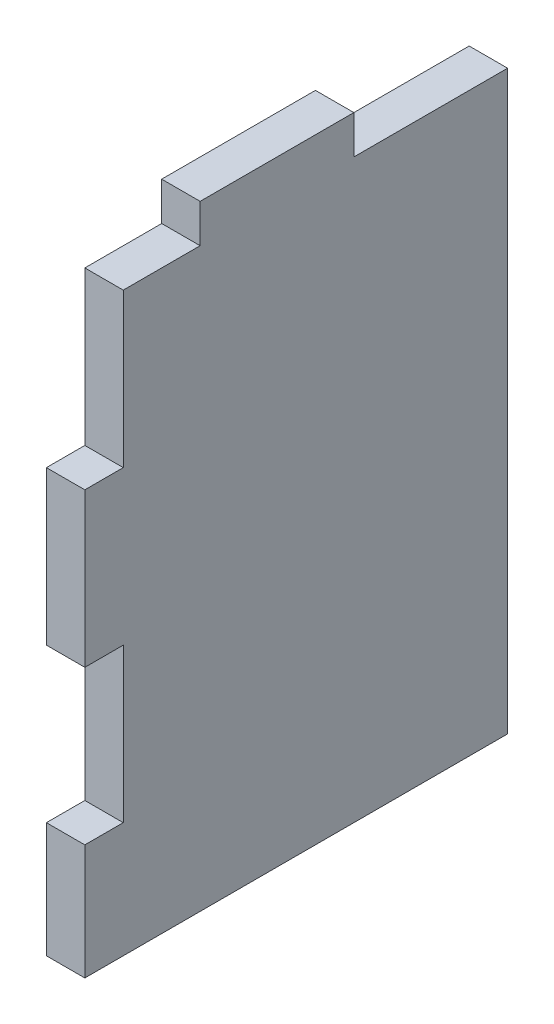
SolidWorks part; units mm, degrees
ref_plane "Front Plane" through (0, 0, 0) normal (0, 0, 1) x (1, 0, 0)
ref_plane "Top Plane" through (0, 0, 0) normal (0, 1, 0) x (1, 0, 0)
ref_plane "Right Plane" through (0, 0, 0) normal (1, 0, 0) x (0, 0, -1)
sketch "Sketch1" plane through (0, 0, 0) normal (1, 0, 0) x (0, 0, -1)
  line L0 (-3.175, 0) -> (0, 0)
  line L1 (0, 0) -> (31.75, 0)
  line L2 (0, 0) -> (0, 47.625)
  line L3 (0, 47.625) -> (31.75, 47.625)
  line L4 (31.75, 0) -> (31.75, 47.625)
  line L5 (6.35, 47.625) -> (19.05, 47.625)
  line L6 (6.35, 47.625) -> (6.35, 50.8)
  line L7 (6.35, 50.8) -> (19.05, 50.8)
  line L8 (19.05, 47.625) -> (19.05, 50.8)
  line L9 (0, 34.925) -> (-3.175, 34.925)
  line L10 (0, 34.925) -> (0, 22.225)
  line L11 (0, 22.225) -> (-3.175, 22.225)
  line L12 (-3.175, 34.925) -> (-3.175, 22.225)
  line L13 (0, 9.525) -> (-3.175, 9.525)
  line L14 (0, 9.525) -> (0, 0)
  line L16 (-3.175, 9.525) -> (-3.175, 0)
  dimension "D1" = 12.7
  dimension "D2" = 6.35
  dimension "D3" = 3.175
  dimension "D4" = 12.7
  dimension "D5" = 12.7
  dimension "D6" = 3.175
  dimension "D7" = 47.625
  dimension "D8" = 3.175
  dimension "D9" = 9.525
  dimension "D10" = 31.75
  dimension "D11" = 12.7
extrude "Boss-Extrude1" add sketch "Sketch1" along normal blind 3.175 contours L1 L4 L3 L2 | L3 L8 L7 L6 | L13 L16 L0 L2 | L12 L11 L10 L9
